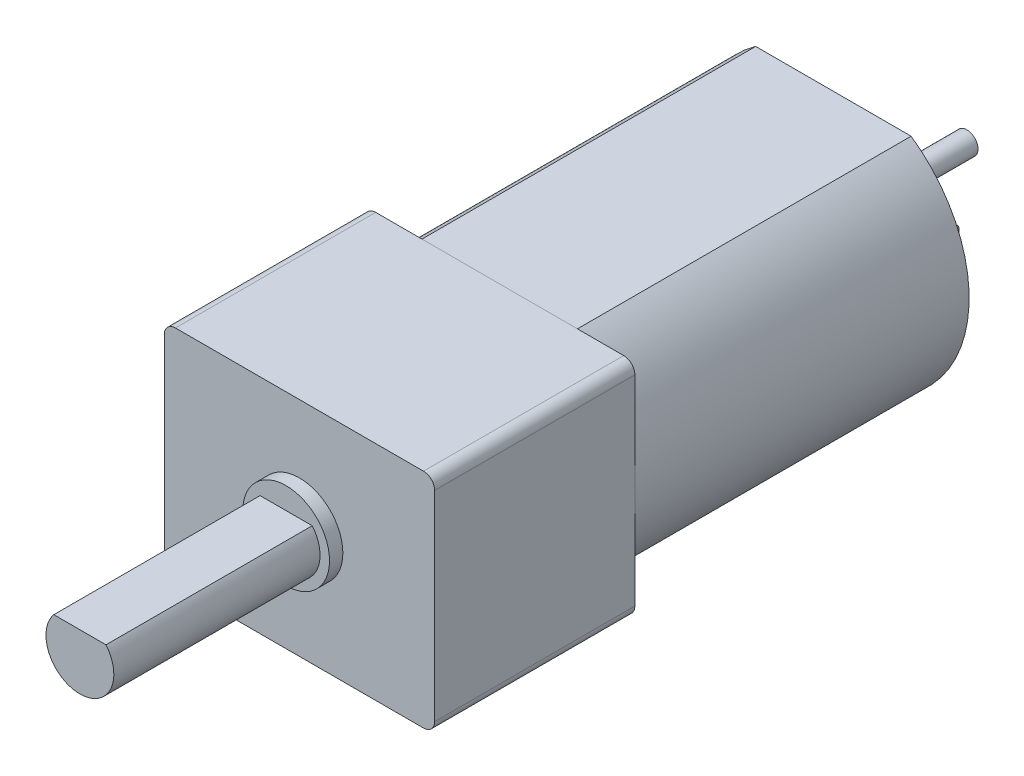
SolidWorks part; units mm, degrees
ref_plane "Front Plane" through (0, 0, 0) normal (0, 0, 1) x (1, 0, 0)
ref_plane "Top Plane" through (0, 0, 0) normal (0, 1, 0) x (1, 0, 0)
ref_plane "Right Plane" through (0, 0, 0) normal (1, 0, 0) x (0, 0, -1)
sketch "Sketch1" plane through (0, 0, 0) normal (0, 0, 1) x (1, 0, 0)
  line L0 (0, 5) -> (0, -5) construction
  line L1 (0, -5) -> (0, 0) construction
  line L7 (-6.075, 5) -> (6.075, 5)
  line L8 (-6.075, 5) -> (-6.075, -5)
  line L9 (-6.075, -5) -> (6.075, -5)
  line L10 (6.075, 5) -> (6.075, -5)
  dimension "D1" = 10
  dimension "D3" = 12.15
extrude "Extrude2" add sketch "Sketch1" against normal blind 9
sketch "Sketch11" plane through (0, 0, 0) normal (0, 0, 1) x (1, 0, 0)
  line L0 (0, 5) -> (0, -5) construction
  line L1 (6.075, 5) -> (-6.075, 5) construction
  line L2 (-6.075, -5) -> (6.075, -5) construction
  line L3 (-6.075, 0) -> (0, 0) construction
  line L4 (-6.075, 5) -> (-6.075, -5) construction
  line L5 (0, 0) -> (6.075, 0) construction
  line L6 (6.075, -5) -> (6.075, 5) construction
  circle A0 centre (0, 0) radius 1.95
  dimension "D1" = 3.9
extrude "Extrude5" add sketch "Sketch11" along normal blind 0.6
sketch "Sketch12" plane through (0, 0, 0.6) normal (0, 0, 1) x (1, 0, 0)
  line L0 (0, 0.975) -> (0, -1.525) construction
  line L1 (0, 0.975) -> (0, -1.525) construction
  line L2 (-1.1726, 0.975) -> (1.1726, 0.975)
  arc A0 (-1.1726, 0.975) -> (1.1726, 0.975) centre (0, 0) ccw
  dimension "D1" = 3.05
  dimension "D2" = 2.3452
extrude "Extrude6" add sketch "Sketch12" along normal blind 9.27
sketch "Sketch13" plane through (0, 0, -9) normal (0, 0, -1) x (-1, 0, 0)
  line L0 (0, 5) -> (0, -5) construction
  line L1 (-6.075, 5) -> (6.075, 5) construction
  line L2 (6.075, -5) -> (-6.075, -5) construction
  line L3 (-6.075, -5) -> (-6.075, 5) construction
  line L4 (-6.075, 0) -> (0, 0) construction
  line L5 (0, 0) -> (6.075, 0) construction
  line L6 (6.075, 5) -> (6.075, -5) construction
  line L7 (0, 5) -> (0, -5) construction
  line L8 (-3.4943, 5) -> (3.4943, 5)
  line L10 (-3.4943, -5) -> (3.4943, -5)
  line L12 (0, -5) -> (0, 0) construction
  arc A0 (-3.4943, 5) -> (-3.4943, -5) centre (0, 0) ccw
  arc A1 (3.4943, -5) -> (3.4943, 5) centre (0, 0) ccw
  dimension "D1" = 12.2
  dimension "D2" = 6.9886
  dimension "D3" = 6.9886
extrude "Extrude7" add sketch "Sketch13" along normal blind 15 separate body
sketch "Sketch14" plane through (0, 0, -24) normal (0, 0, -1) x (-1, 0, 0)
  line L0 (0, 5) -> (0, -5) construction
  line L1 (3.4943, 5) -> (-3.4943, 5) construction
  line L2 (-3.4943, -5) -> (3.4943, -5) construction
  line L3 (0, -5) -> (0, 0) construction
  circle A0 centre (0, 0) radius 2.5
  dimension "D1" = 5
extrude "Extrude8" add sketch "Sketch14" along normal blind 1.5
sketch "Sketch16" plane through (0, 0, -24) normal (0, 0, -1) x (-1, 0, 0)
  line L0 (0, 2.5) -> (0, -2.5) construction
  line L1 (3.35, 0.75) -> (3.65, 0.75)
  line L2 (3.35, 0.75) -> (3.35, -0.75)
  line L3 (3.35, -0.75) -> (3.65, -0.75)
  line L4 (3.65, 0.75) -> (3.65, -0.75)
  line L5 (0, -2.5) -> (0, 0) construction
  line L6 (3.5, 0.75) -> (3.5, -0.75) construction
  line L7 (3.5, -0.75) -> (3.5, 0) construction
  circle A0 centre (0, 0) radius 2.5 construction
  dimension "D1" = 0.3
  dimension "D2" = 1.5
  dimension "D3" = 3.5
extrude "Extrude10" add sketch "Sketch16" along normal blind 2
fillet "Fillet1" radius 0.3 2 edges at (-3.5, -0.75, -26) (-3.5, 0.75, -26)
fillet "Fillet2" radius 0.5 4 edges at (6.075, -5, -4.5) (-6.075, -5, -4.5) (-6.075, 5, -4.5) (6.075, 5, -4.5)
fillet "Fillet3" radius 0.3 1 edges at (-2.5, 0, -25.5)
sketch "Sketch17" plane through (0, 0, -25.5) normal (0, 0, -1) x (-1, 0, 0)
  circle A0 centre (0, 0) radius 0.5
extrude "Extrude11" add sketch "Sketch17" along normal blind 4.5
mirror "Mirror2" about plane through (0, 0, 0) normal (1, 0, 0) of "Fillet1", "Extrude10"
